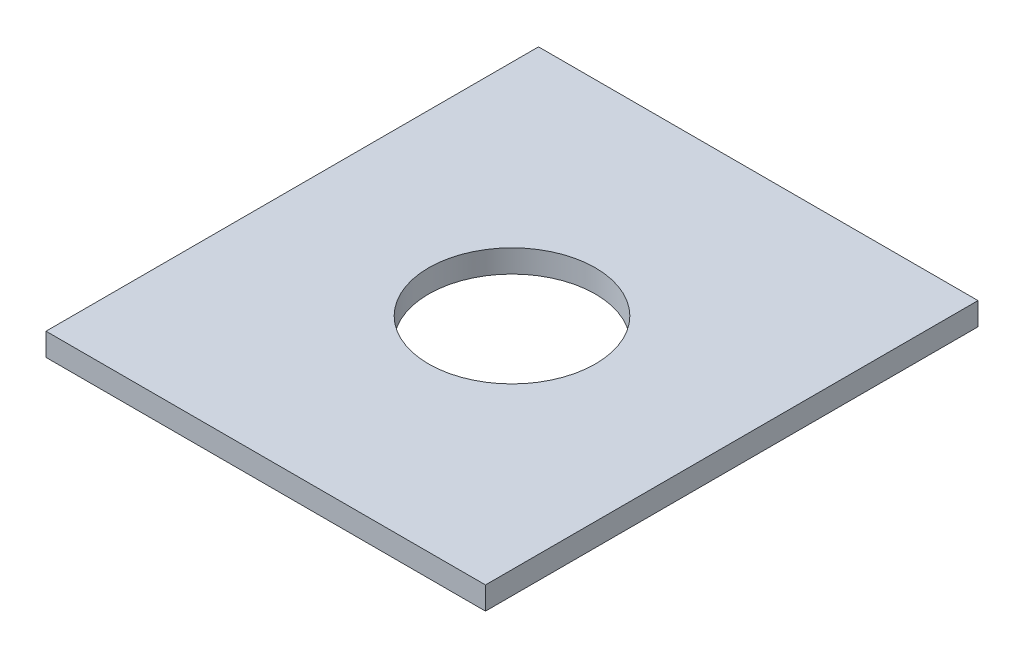
SolidWorks part; units mm, degrees
ref_plane "Front Plane" through (0, 0, 0) normal (0, 0, 1) x (1, 0, 0)
ref_plane "Top Plane" through (0, 0, 0) normal (0, 1, 0) x (1, 0, 0)
ref_plane "Right Plane" through (0, 0, 0) normal (1, 0, 0) x (0, 0, -1)
sketch "Sketch3" plane through (0, 0, 0) normal (0, 1, 0) x (1, 0, 0)
  line L0 (-29, -32.5) -> (29, -32.5)
  line L1 (29, -32.5) -> (29, 32.5)
  line L2 (29, 32.5) -> (-29, 32.5)
  line L3 (-29, 32.5) -> (-29, -32.5)
  circle A0 centre (0, 0) radius 11
  point P6 (0, 0)
  point P8 (2.0442, -1.1067)
  dimension "D3" = 22
  dimension "D1" = 65
  dimension "D2" = 58
  dimension "D4" = 29
  dimension "D5" = 32.5
extrude "Boss-Extrude1" add sketch "Sketch3" along normal blind 3
